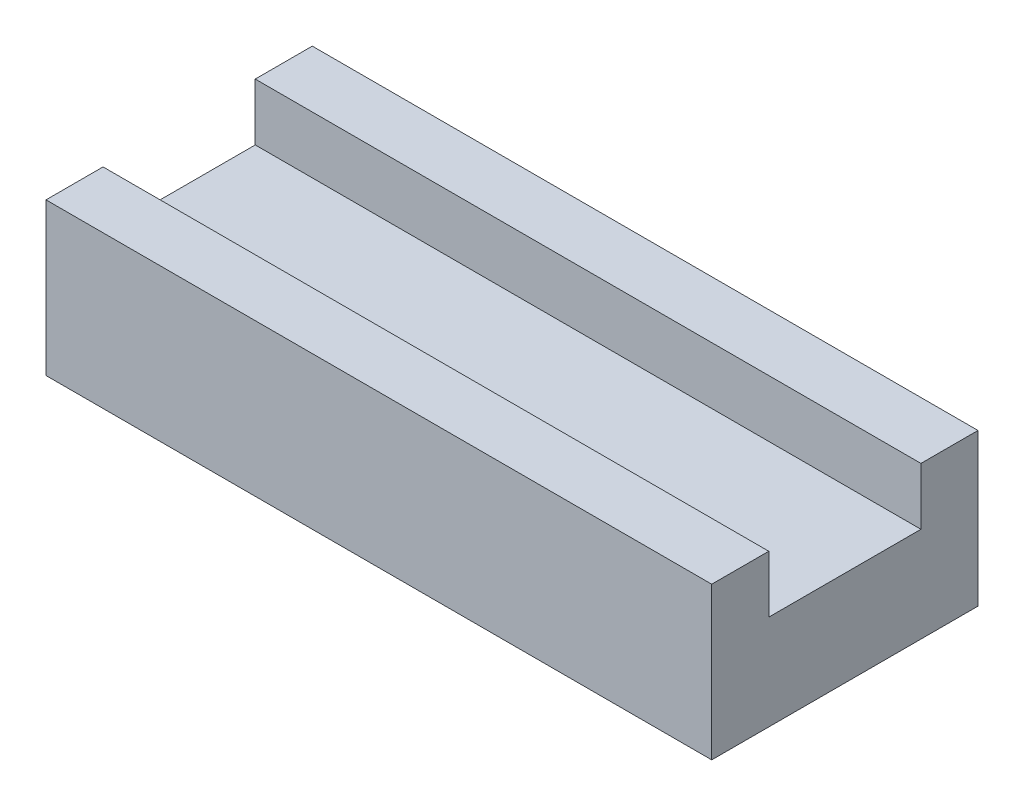
SolidWorks part; units mm, degrees
ref_plane "Front Plane" through (0, 0, 0) normal (0, 0, 1) x (1, 0, 0)
ref_plane "Top Plane" through (0, 0, 0) normal (0, 1, 0) x (1, 0, 0)
ref_plane "Right Plane" through (0, 0, 0) normal (1, 0, 0) x (0, 0, -1)
sketch "Sketch1" plane through (0, 0, 0) normal (1, 0, 0) x (0, 0, -1)
  line L0 (-7, 2.5) -> (-7, 5.5)
  line L1 (-7, -2.5) -> (7, -2.5)
  line L2 (-7, -2.5) -> (-7, 2.5)
  line L3 (-4, 2.5) -> (4, 2.5)
  line L4 (7, -2.5) -> (7, 2.5)
  line L5 (-7, -2.5) -> (7, 2.5) construction
  line L6 (-7, 2.5) -> (7, -2.5) construction
  line L7 (-7, 5.5) -> (-4, 5.5)
  line L8 (-4, 5.5) -> (-4, 2.5)
  line L9 (7, 2.5) -> (7, 5.5)
  line L10 (7, 5.5) -> (4, 5.5)
  line L11 (4, 5.5) -> (4, 2.5)
  point P0 (0, 0)
  point P12 (0, 2.5)
  point P13 (-4, 1.3048)
  point P14 (0, 0)
  point P15 (-7, 2.3631)
  dimension "D1" = 5
  dimension "D2" = 8
  dimension "D3" = 3
  dimension "D4" = 3
extrude "Boss-Extrude1" add sketch "Sketch1" against normal blind 35
